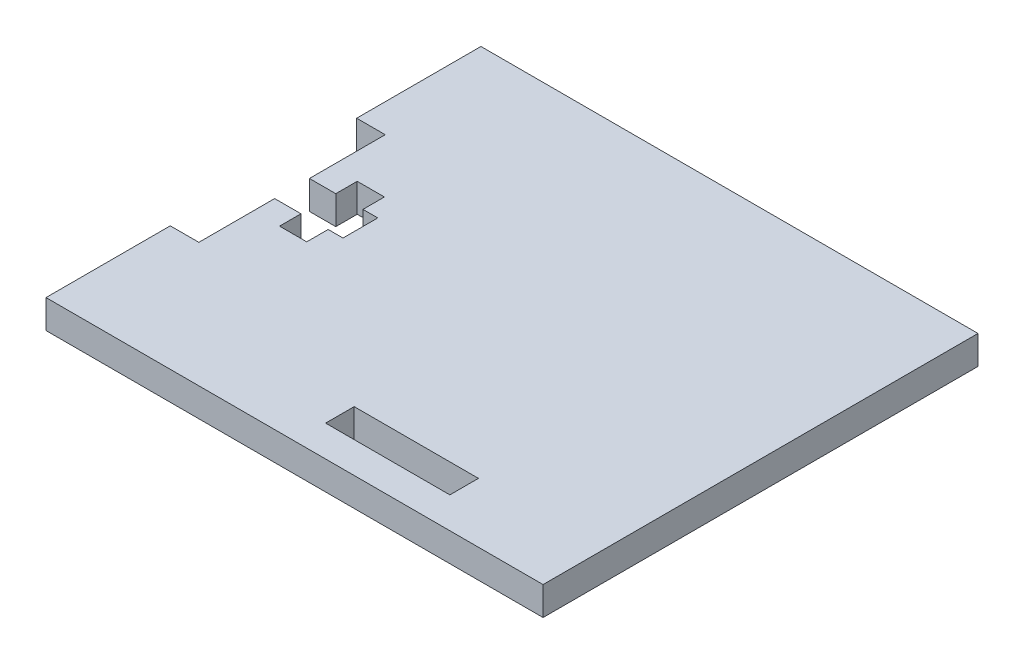
SolidWorks part; units mm, degrees
ref_plane "Front Plane" through (0, 0, 0) normal (0, 0, 1) x (1, 0, 0)
ref_plane "Top Plane" through (0, 0, 0) normal (0, 1, 0) x (1, 0, 0)
ref_plane "Right Plane" through (0, 0, 0) normal (1, 0, 0) x (0, 0, -1)
sketch "Sketch1" plane through (0, 0, 0) normal (0, 1, 0) x (1, 0, 0)
  line L0 (0, 31.75) -> (0, 44.45)
  line L1 (0, 0) -> (50.8, 0)
  line L2 (0, 0) -> (0, 12.7)
  line L3 (0, 44.45) -> (50.8, 44.45)
  line L4 (50.8, 0) -> (50.8, 44.45)
  line L5 (0, 12.7) -> (2.921, 12.7)
  line L6 (50.8, 22.225) -> (9.906, 22.225) construction
  line L7 (0, 31.75) -> (2.921, 31.75)
  line L8 (2.921, 12.7) -> (2.921, 20.447)
  line L9 (2.921, 20.447) -> (5.6123, 20.447)
  line L10 (5.6123, 24.003) -> (5.6123, 26.1937)
  line L11 (2.921, 24.003) -> (5.6123, 24.003)
  line L12 (9.906, 20.447) -> (9.906, 24.003)
  line L13 (2.921, 24.003) -> (2.921, 31.75)
  line L14 (5.6123, 18.2562) -> (8.3905, 18.2562)
  line L15 (5.6123, 18.2562) -> (5.6123, 20.447)
  line L16 (5.6123, 26.1937) -> (8.3905, 26.1937)
  line L17 (8.3905, 18.2562) -> (8.3905, 20.447)
  line L19 (25.4, 6.096) -> (38.1, 6.096)
  line L20 (25.4, 6.096) -> (25.4, 3.175)
  line L22 (8.3905, 24.003) -> (8.3905, 26.1937)
  line L24 (8.3905, 20.447) -> (9.906, 20.447)
  line L25 (8.3905, 24.003) -> (9.906, 24.003)
  line L26 (25.4, 3.175) -> (38.1, 3.175)
  line L27 (38.1, 6.096) -> (38.1, 3.175)
  point P5 (0, 22.225)
  point P16 (7.0014, 22.225)
  dimension "D1" = 50.8
  dimension "D2" = 44.45
  dimension "D3" = 19.05
  dimension "D4" = 2.921
  dimension "D5" = 12.7
  dimension "D6" = 1.778
  dimension "D7" = 3.556
  dimension "D8" = 6.985
  dimension "D9" = 7.9375
  dimension "D10" = 2.7781
  dimension "D11" = 2.921
  dimension "D12" = 12.7
  dimension "D13" = 3.175
  dimension "D14" = 25.4
extrude "Boss-Extrude1" add sketch "Sketch1" along normal blind 2.921
